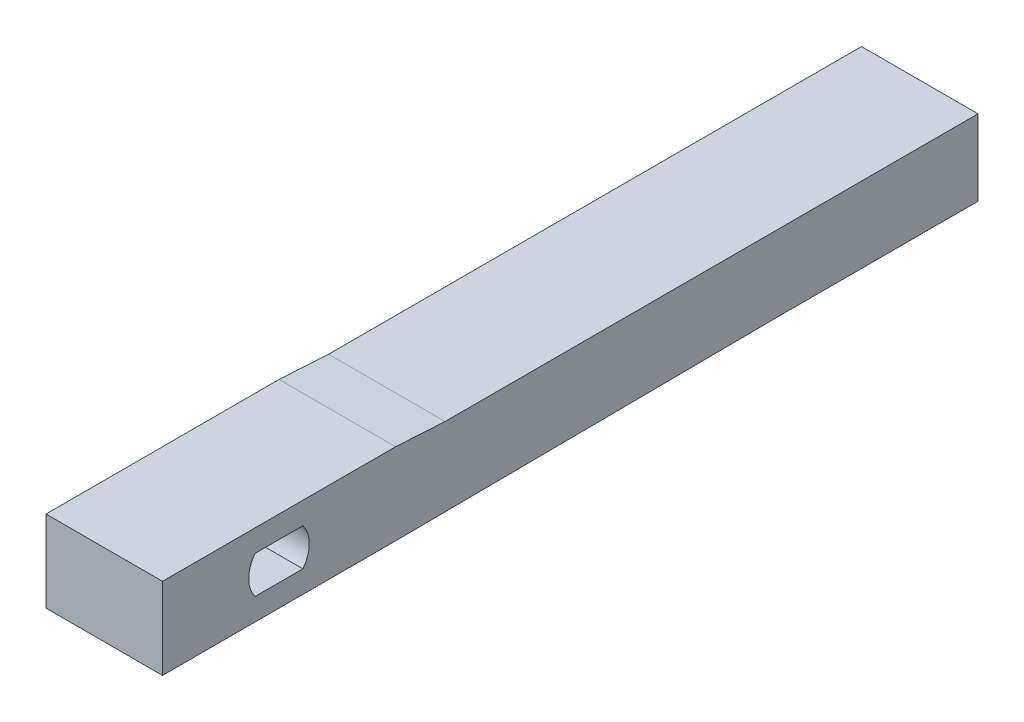
SolidWorks part; units mm, degrees
ref_plane "Front Plane" through (0, 0, 0) normal (0, 0, 1) x (1, 0, 0)
ref_plane "Top Plane" through (0, 0, 0) normal (0, 1, 0) x (1, 0, 0)
ref_plane "Right Plane" through (0, 0, 0) normal (1, 0, 0) x (0, 0, -1)
sketch "Sketch1" plane through (-4, 0, 0) normal (-1, 0, 0) x (0, 0, 1)
  line L0 (2, 6.5) -> (-2, 6.5)
  line L1 (2, 6.5) -> (-2, 6.5) construction
  line L2 (-2, 9.5) -> (2, 9.5)
  line L3 (-2, 9.5) -> (2, 9.5) construction
  line L4 (0, 8) -> (-36.4984, 8) construction
  line L5 (-10, 11.5) -> (10, 11.5)
  line L7 (-10, 4.5) -> (10, 4.5)
  line L8 (10, 11.5) -> (10, 4.5)
  line L9 (-14.2609, 11.25) -> (-10, 11.5)
  line L14 (-60, 11.25) -> (-14.2609, 11.25)
  line L15 (-60, 11.25) -> (-60, 4.75)
  line L16 (-60, 4.75) -> (-42.6359, 4.75)
  line L18 (-42.6359, 4.75) -> (-10, 4.5)
  line L19 (-2.0494, 9.6) -> (2.0494, 9.6)
  line L20 (2.0494, 6.4) -> (-2.0494, 6.4)
  arc A0 (2, 9.5) -> (-2, 9.5) centre (0, 8) ccw
  arc A1 (-2, 9.5) -> (-2, 6.5) centre (0, 8) ccw
  arc A2 (-2, 6.5) -> (2, 6.5) centre (0, 8) ccw
  arc A3 (2, 6.5) -> (2, 9.5) centre (0, 8) ccw
  arc A4 (2, 6.5) -> (2, 9.5) centre (0, 8) ccw construction
  arc A5 (2.0494, 6.4) -> (2.0494, 9.6) centre (0, 8) ccw
  arc A6 (-2, 9.5) -> (-2, 6.5) centre (0, 8) ccw construction
  arc A7 (-2.0494, 9.6) -> (-2.0494, 6.4) centre (0, 8) ccw
  dimension "D1" = 2
  dimension "D2" = 20
  dimension "D3" = 10
  dimension "D4" = 6.5
  dimension "D5" = 70
  dimension "D6" = 0.1
extrude "Boss-Extrude1" add sketch "Sketch1" along normal blind 10
